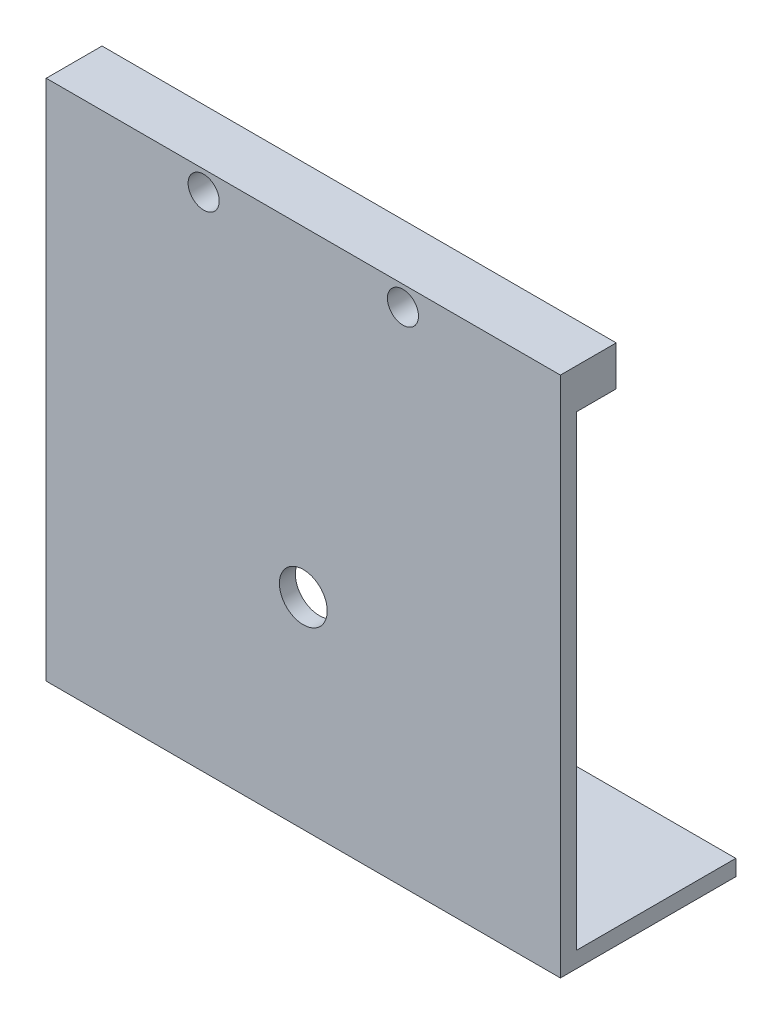
SolidWorks part; units mm, degrees
ref_plane "Alzado" through (0, 0, 0) normal (0, 0, 1) x (1, 0, 0)
ref_plane "Planta" through (0, 0, 0) normal (0, 1, 0) x (1, 0, 0)
ref_plane "Vista lateral" through (0, 0, 0) normal (1, 0, 0) x (0, 0, -1)
sketch "Croquis1" plane through (0, 0, 0) normal (0, 0, 1) x (1, 0, 0)
  line L1 (32.25, -26.75) -> (-32.25, -26.75)
  line L2 (32.25, -26.75) -> (32.25, 26.75)
  line L3 (32.25, 26.75) -> (-32.25, 26.75)
  line L4 (-32.25, -26.75) -> (-32.25, 26.75)
  line L5 (32.25, -26.75) -> (-32.25, 26.75) construction
  line L6 (32.25, 26.75) -> (-32.25, -26.75) construction
  point P0 (0, 0)
  dimension "D1" = 53.5
  dimension "D2" = 64.5
extrude "Saliente-Extruir1" add sketch "Croquis1" along normal blind 2
sketch "Croquis2" plane through (0, 0, 0) normal (0, 0, -1) x (-1, 0, 0)
  line L0 (32.25, 26.75) -> (32.25, -26.75) construction
  line L1 (-32.25, 26.75) -> (32.25, 26.75)
  line L2 (-32.25, 26.75) -> (-32.25, 21.75)
  line L3 (-32.25, 21.75) -> (32.25, 21.75)
  line L4 (32.25, 26.75) -> (32.25, 21.75)
  line L5 (-32.25, 26.75) -> (32.25, 21.75) construction
  line L6 (-32.25, 21.75) -> (32.25, 26.75) construction
  point P4 (0, 24.25)
  dimension "D1" = 5
extrude "Saliente-Extruir2" add sketch "Croquis2" along normal blind 5
sketch "Croquis3" plane through (0, 0, 0) normal (0, 0, -1) x (-1, 0, 0)
  line L0 (32.25, 21.75) -> (32.25, -26.75) construction
  line L1 (-32.25, -26.75) -> (32.25, -26.75)
  line L2 (-32.25, -26.75) -> (-32.25, -24.75)
  line L3 (-32.25, -24.75) -> (32.25, -24.75)
  line L4 (32.25, -26.75) -> (32.25, -24.75)
  line L5 (-32.25, -26.75) -> (32.25, -24.75) construction
  line L6 (-32.25, -24.75) -> (32.25, -26.75) construction
  point P4 (0, -25.75)
  dimension "D1" = 2
extrude "Saliente-Extruir3" add sketch "Croquis3" along normal blind 20
sketch "Croquis5" plane through (0, 0, 0) normal (0, 0, -1) x (-1, 0, 0)
  line L0 (0, -24.75) -> (0, 21.75) construction
  line L1 (32.25, -24.75) -> (-32.25, -24.75) construction
  line L2 (-32.25, 21.75) -> (32.25, 21.75) construction
  circle A0 centre (0, -1.5) radius 3
  dimension "D1" = 6
extrude "Cortar-Extruir1" cut sketch "Croquis5" against normal blind 20
sketch "Croquis7" plane through (32.25, 0, 0) normal (1, 0, 0) x (0, 0, -1)
  line L0 (0, 21.75) -> (0, 21.3522) construction
  line L1 (0, 21.3522) -> (5, 21.3522)
  line L2 (5, 26.75) -> (5, 21.75) construction
  line L3 (0, 21.3522) -> (0, 26.75)
  line L4 (-2, 26.75) -> (5, 26.75) construction
  line L5 (0, 26.75) -> (5, 26.75)
  line L6 (5, 26.75) -> (5, 21.3522)
extrude "Cortar-Extruir3" cut sketch "Croquis7" against normal through all
sketch "Croquis8" plane through (32.25, 0, 0) normal (1, 0, 0) x (0, 0, -1)
  line L0 (0, 23.75) -> (0, 33.75) construction
  line L3 (-2, -26.75) -> (-2, 26.75) construction
  line L4 (0, 33.75) -> (-2, 33.75)
  line L5 (0, 33.75) -> (0, 23.75)
  line L6 (0, 23.75) -> (-2, 23.75)
  line L7 (-2, 33.75) -> (-2, 23.75)
  line L8 (0, 33.75) -> (-2, 23.75) construction
  line L9 (0, 23.75) -> (-2, 33.75) construction
  line L11 (-2, 33.75) -> (0, 33.75)
  line L12 (-2, 33.75) -> (-2, 38.75)
  line L13 (-2, 38.75) -> (0, 38.75)
  line L14 (0, 33.75) -> (0, 38.75)
  line L15 (-2, 33.75) -> (0, 38.75) construction
  line L16 (-2, 38.75) -> (0, 33.75) construction
  line L17 (0, 38.75) -> (5, 38.75)
  line L18 (0, 38.75) -> (0, 33.75)
  line L19 (0, 33.75) -> (5, 33.75)
  line L20 (5, 38.75) -> (5, 33.75)
  line L21 (0, 38.75) -> (5, 33.75) construction
  line L22 (0, 33.75) -> (5, 38.75) construction
  line L23 (-2, -26.75) -> (20, -26.75) construction
  point P4 (-1, 28.75)
  point P12 (-1, 36.25)
  point P15 (2.5, 36.25)
  point P18 (0, 0)
  dimension "D1" = 10
  dimension "D2" = 5
  dimension "D3" = 5
  dimension "D4" = 50.5
  dimension "D5" = 2
extrude "Saliente-Extruir4" add sketch "Croquis8" against normal through all contours L5 L4 L7 L6 | L12 L11 L14 L13 | L18 L17 L20 L19
sketch "Croquis9" plane through (0, 0, -5) normal (0, 0, -1) x (-1, 0, 0)
  line L0 (0, 38.75) -> (0, 33.75) construction
  line L1 (32.25, 38.75) -> (-32.25, 38.75) construction
  line L2 (32.25, 33.75) -> (-32.25, 33.75) construction
  line L3 (-12.5, 36.25) -> (12.5, 36.25) construction
  circle A0 centre (-12.5, 36.25) radius 1.95
  circle A1 centre (12.5, 36.25) radius 1.95
  point P9 (0, 34.9234)
  point P10 (0, 36.25)
  dimension "D2" = 3.9
  dimension "D1" = 25
extrude "Cortar-Extruir4" cut sketch "Croquis9" against normal through all
